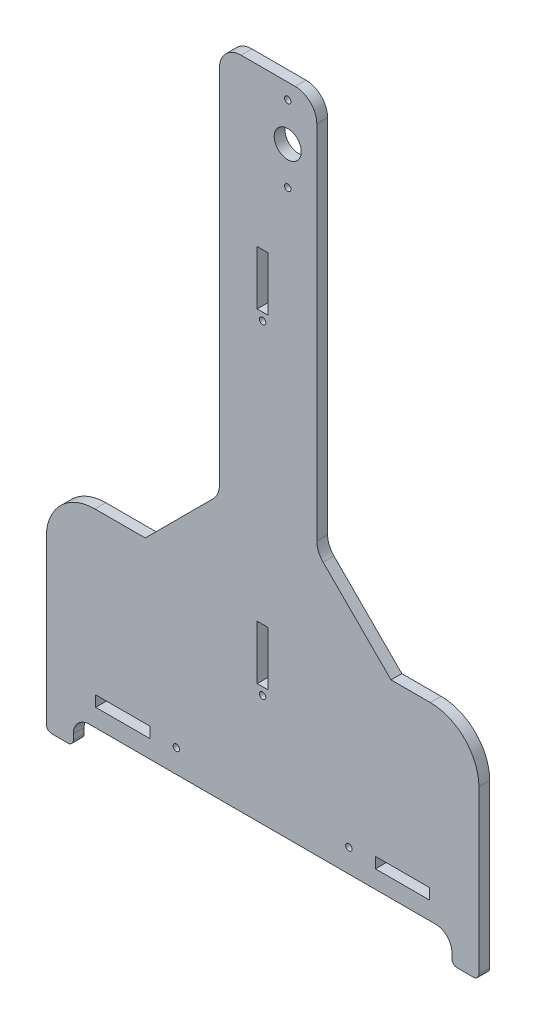
SolidWorks part; units mm, degrees
ref_plane "Front Plane" through (0, 0, 0) normal (0, 0, 1) x (1, 0, 0)
ref_plane "Top Plane" through (0, 0, 0) normal (0, 1, 0) x (1, 0, 0)
ref_plane "Right Plane" through (0, 0, 0) normal (1, 0, 0) x (0, 0, -1)
sketch "Sketch1" plane through (0, 0, 0) normal (0, 0, 1) x (1, 0, 0)
  line L0 (-51.0408, -12.4156) -> (-51.0408, -9.8756)
  line L1 (-61.2008, -14.9556) -> (-53.5808, -14.9556)
  line L2 (-63.7408, -12.4156) -> (-63.7408, 63.7844)
  line L3 (98.1877, 86.6444) -> (116.5992, 86.6444)
  line L4 (139.4592, -12.4156) -> (139.4592, 63.7844)
  line L5 (37.8592, -14.9556) -> (37.8592, -7.6409) construction
  line L6 (126.7592, -12.4156) -> (126.7592, -9.8756)
  line L7 (-43.4208, -2.2556) -> (119.1392, -2.2556)
  line L8 (129.2992, -14.9556) -> (136.9192, -14.9556)
  line L9 (37.8592, -2.2556) -> (37.8592, 34.4315) construction
  line L10 (-63.7408, 50.0824) -> (139.4592, 50.0824) construction
  line L11 (-15.1177, 11.1964) -> (-40.5177, 6.1164) construction
  line L12 (90.8361, 6.1164) -> (116.2361, 6.1164)
  line L13 (90.8361, 6.1164) -> (90.8361, 11.1964)
  line L14 (90.8361, 11.1964) -> (116.2361, 11.1964)
  line L15 (116.2361, 6.1164) -> (116.2361, 11.1964)
  line L16 (90.8361, 6.1164) -> (116.2361, 11.1964) construction
  line L17 (90.8361, 11.1964) -> (116.2361, 6.1164) construction
  line L18 (-15.1177, 6.1164) -> (-40.5177, 11.1964) construction
  line L19 (-40.5177, 6.1164) -> (-40.5177, 11.1964)
  line L20 (-15.1177, 11.1964) -> (-40.5177, 11.1964)
  line L21 (-15.1177, 6.1164) -> (-15.1177, 11.1964)
  line L22 (-15.1177, 6.1164) -> (-40.5177, 6.1164)
  line L23 (-17.2564, 86.6444) -> (14.6389, 118.5397)
  line L24 (35.3192, 53.6891) -> (40.3992, 53.6891)
  line L25 (35.3192, 53.6891) -> (35.3192, 79.0891)
  line L26 (35.3192, 79.0891) -> (40.3992, 79.0891)
  line L27 (40.3992, 53.6891) -> (40.3992, 79.0891)
  line L28 (35.3192, 53.6891) -> (40.3992, 79.0891) construction
  line L29 (35.3192, 79.0891) -> (40.3992, 53.6891) construction
  line L30 (17.6147, 125.7239) -> (17.6147, 295.3682)
  line L31 (27.7747, 305.5282) -> (53.1565, 305.5282)
  line L34 (98.1877, 86.6444) -> (66.2923, 118.5397)
  line L35 (63.3165, 125.7239) -> (63.3165, 295.3682)
  line L37 (-17.2564, 86.6444) -> (-40.8808, 86.6444)
  line L38 (40.3992, 206.0891) -> (40.3992, 231.4891)
  line L39 (35.3192, 206.0891) -> (40.3992, 206.0891)
  line L40 (35.3192, 206.0891) -> (35.3192, 231.4891)
  line L41 (35.3192, 231.4891) -> (40.3992, 231.4891)
  arc A0 (126.7592, -9.8756) -> (119.1392, -2.2556) centre (119.1392, -9.8756) ccw
  arc A1 (-51.0408, -9.8756) -> (-43.4208, -2.2556) centre (-43.4208, -9.8756) cw
  arc A2 (126.7592, -12.4156) -> (129.2992, -14.9556) centre (129.2992, -12.4156) ccw
  arc A3 (136.9192, -14.9556) -> (139.4592, -12.4156) centre (136.9192, -12.4156) ccw
  arc A4 (-51.0408, -12.4156) -> (-53.5808, -14.9556) centre (-53.5808, -12.4156) cw
  arc A5 (-61.2008, -14.9556) -> (-63.7408, -12.4156) centre (-61.2008, -12.4156) cw
  arc A6 (116.5992, 86.6444) -> (139.4592, 63.7844) centre (116.5992, 63.7844) cw
  arc A7 (-63.7408, 63.7844) -> (-40.8808, 86.6444) centre (-40.8808, 63.7844) cw
  circle A8 centre (37.8592, 50.0824) radius 1.5
  circle A9 centre (78.3788, 8.6564) radius 1.5
  circle A10 centre (-2.6604, 8.6564) radius 1.5
  circle A11 centre (49.6707, 298.3104) radius 1.5
  circle A12 centre (49.6707, 262.6064) radius 1.5
  circle A13 centre (49.6707, 280.2946) radius 6.35
  arc A14 (66.2923, 118.5397) -> (63.3165, 125.7239) centre (73.4765, 125.7239) cw
  arc A15 (14.6389, 118.5397) -> (17.6147, 125.7239) centre (7.4547, 125.7239) ccw
  arc A16 (63.3165, 295.3682) -> (53.1565, 305.5282) centre (53.1565, 295.3682) ccw
  arc A17 (27.7747, 305.5282) -> (17.6147, 295.3682) centre (27.7747, 295.3682) ccw
  circle A18 centre (37.8592, 202.4824) radius 1.5
  point P37 (103.5361, 8.6564)
  point P46 (-27.8177, 8.6564)
  point P47 (37.8592, 66.3891)
  dimension "D5" = 7.62
  dimension "D6" = 2.54
  dimension "D7" = 22.86
  dimension "D12" = 3
  dimension "D13" = 3
  dimension "D14" = 3
  dimension "D15" = 3
  dimension "D16" = 12.7
  dimension "D17" = 10.16
  dimension "D3" = 12.7
  dimension "D8" = 5.08
  dimension "D9" = 25.4
  dimension "D10" = 25.4
  dimension "D11" = 5.08
  dimension "D18" = 2
  dimension "D19" = 2
extrude "Boss-Extrude1" add sketch "Sketch1" along normal blind 5.08
